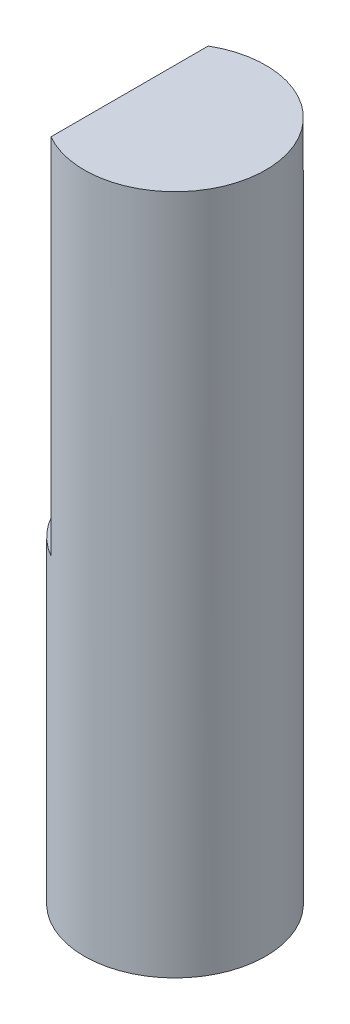
SolidWorks part; units mm, degrees
ref_plane "Front Plane" through (0, 0, 0) normal (0, 0, 1) x (1, 0, 0)
ref_plane "Top Plane" through (0, 0, 0) normal (0, 1, 0) x (1, 0, 0)
ref_plane "Right Plane" through (0, 0, 0) normal (1, 0, 0) x (0, 0, -1)
sketch "Sketch1" plane through (0, 0, 0) normal (0, 1, 0) x (1, 0, 0)
  circle A0 centre (0, 0) radius 2
extrude "Boss-Extrude1" add sketch "Sketch1" along normal blind 15
sketch "Sketch2" plane through (0, 15, 0) normal (0, 1, 0) x (1, 0, 0)
  line L0 (-1, 1.7321) -> (-1, -1.7321)
  arc A0 (-1, 1.7321) -> (-1, -1.7321) centre (0, 0) ccw
  dimension "D1" = 1
  dimension "D2" = 4
extrude "Cut-Extrude1" cut sketch "Sketch2" against normal blind 8
